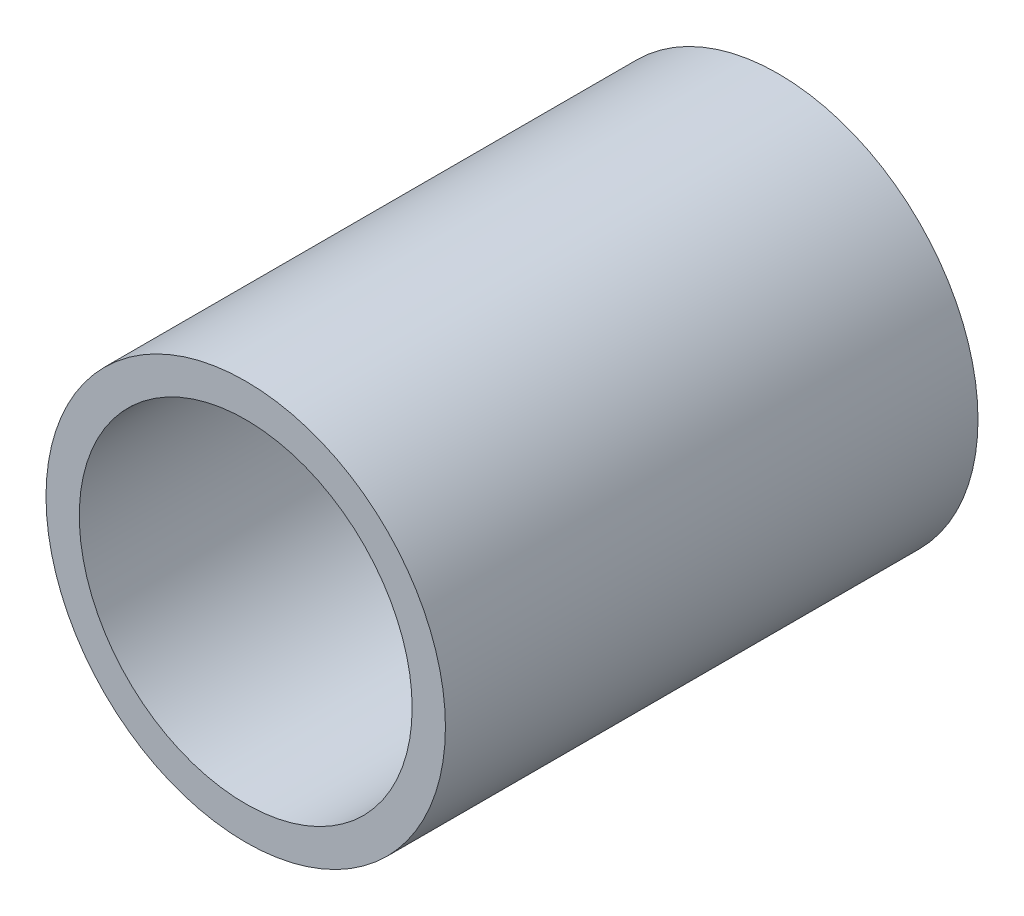
SolidWorks part; units mm, degrees
ref_plane "Front Plane" through (0, 0, 0) normal (0, 0, 1) x (1, 0, 0)
ref_plane "Top Plane" through (0, 0, 0) normal (0, 1, 0) x (1, 0, 0)
ref_plane "Right Plane" through (0, 0, 0) normal (1, 0, 0) x (0, 0, -1)
sketch "Sketch1" plane through (0, 0, 0) normal (0, 0, 1) x (1, 0, 0)
  circle A0 centre (0, 0) radius 3.9688
  circle A1 centre (0, 0) radius 4.7625
  dimension "D1" = 7.9375
  dimension "D2" = 9.525
extrude "Extrude1" add sketch "Sketch1" along normal mid plane 12.7
